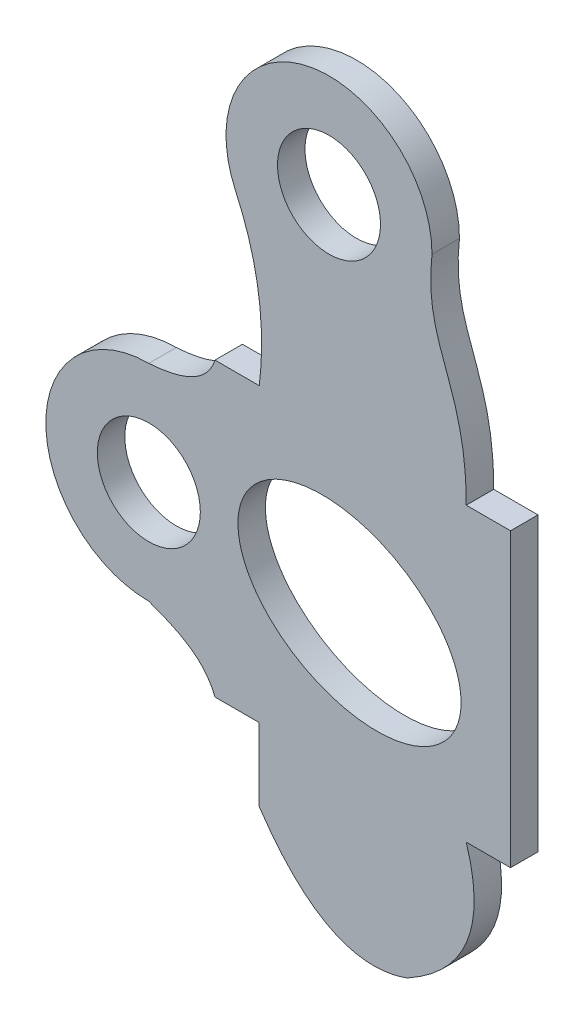
SolidWorks part; units mm, degrees
ref_plane "Front Plane" through (0, 0, 0) normal (0, 0, 1) x (1, 0, 0)
ref_plane "Top Plane" through (0, 0, 0) normal (0, 1, 0) x (1, 0, 0)
ref_plane "Right Plane" through (0, 0, 0) normal (1, 0, 0) x (0, 0, -1)
sketch "Sketch1" plane through (0, 0, 0) normal (0, 0, 1) x (1, 0, 0)
  line L0 (-1815.6119, -965.377) -> (-748.9452, -965.377) construction
  line L1 (10.5755, -30.0334) -> (-6.6445, -30.0334) construction
  line L2 (7.9955, -28.1038) -> (-4.0645, -28.1038) construction
  line L3 (-4.0645, -28.6645) -> (-4.0645, -32.9044)
  line L4 (-6.6445, -11.6645) -> (-4.0645, -11.6645)
  line L6 (7.9955, -11.6645) -> (10.5755, -11.6645)
  line L9 (-6.6445, -28.6645) -> (-4.0645, -28.6645)
  line L11 (10.5755, -11.6645) -> (10.5755, -28.6645)
  line L12 (10.5755, -28.6645) -> (7.9955, -28.6645)
  circle A0 centre (0, 0) radius 3
  arc A1 (6, 0) -> (-5.4344, -2.543) centre (0, 0) ccw
  arc A3 (-10.4964, -13.7566) -> (-10.4964, -25.7566) centre (-10.4964, -19.7566) ccw
  circle A4 centre (-10.4964, -19.7566) radius 3
  ellipse E0 centre (1.1945, -20.5012) end of major axis (-5.0183, -17.8113) minor radius 4.8106
  spline S0 degree 3 poles (-10.4964, -25.7566) (-8.7697, -26.394) (-7.2689, -27.0536) (-6.6445, -28.6645) knots 0 0 0 0 1 1 1 1
  spline S1 degree 2 poles (-5.4689, -2.468) (-3.465, -6.8013) (-4.0645, -11.6645) knots 0 0 0 1 1 1
  spline S2 degree 3 poles (-4.0645, -32.9044) (-1.3655, -36.9178) (1.5363, -38.3434) (4.5568, -37.2381) knots 0 0 0 0 1 1 1 1
  spline S3 degree 2 poles (-6.6445, -11.6645) (-7.2176, -13.5444) (-10.4964, -13.7566) knots 0 0 0 1 1 1
  spline S5 degree 3 poles (4.5568, -37.2381) (7.3535, -35.6947) (9.4109, -33.1467) (7.9955, -28.6645) knots 0 0 0 0 1 1 1 1
  spline S6 degree 2 poles (7.1841, -34.6289) (7.2978, -34.508) (7.4073, -34.3988) knots 0.976425 0.976425 0.976425 1 1 1
  spline S7 degree 3 poles (6, 0) (5.4539, -4.8147) (8.0103, -5.602) (7.9955, -11.6645) knots 0 0 0 0 1 1 1 1
  dimension "D1" = 6
  dimension "D2" = 12
  dimension "D3" = 17.22
  dimension "D4" = 12
  dimension "D8" = 6
  dimension "D5" = 12.06
  dimension "D6" = 2.58
  dimension "D7" = 2.58
  dimension "D9" = 12.06
extrude "Boss-Extrude1" add sketch "Sketch1" along normal blind 1.6
